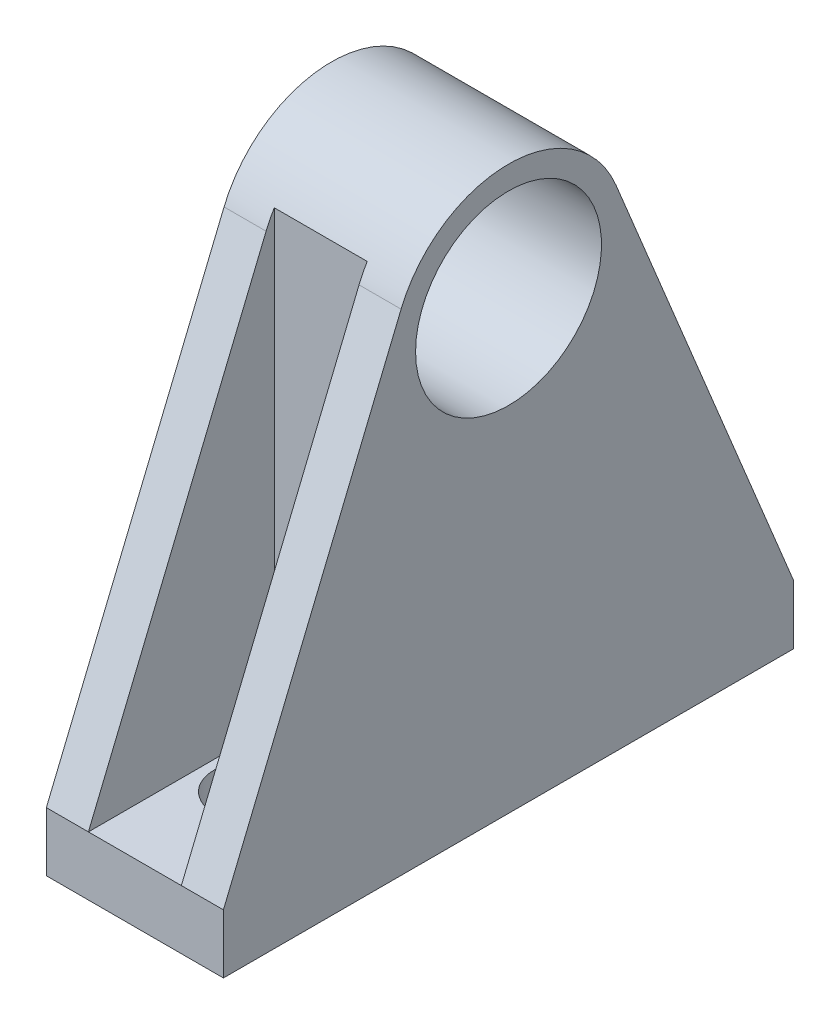
SolidWorks part; units mm, degrees
ref_plane "Front Plane" through (0, 0, 0) normal (0, 0, 1) x (1, 0, 0)
ref_plane "Top Plane" through (0, 0, 0) normal (0, 1, 0) x (1, 0, 0)
ref_plane "Right Plane" through (0, 0, 0) normal (1, 0, 0) x (0, 0, -1)
sketch "Sketch1" plane through (0, 0, 0) normal (1, 0, 0) x (0, 0, -1)
  line L0 (0, 0) -> (0, 48) construction
  line L5 (-30.675, 0) -> (-30.675, 6.35)
  line L8 (30.675, 0) -> (30.675, 6.35)
  line L11 (-30.675, 6.35) -> (-11.5579, 52.7608)
  line L12 (30.675, 6.35) -> (11.5579, 52.7608)
  line L13 (-30.675, 0) -> (30.675, 0)
  circle A0 centre (0, 48) radius 10
  arc A1 (11.5579, 52.7608) -> (-11.5579, 52.7608) centre (0, 48) ccw
  dimension "D1" = 48
  dimension "D2" = 20
  dimension "D3" = 25
  dimension "D4" = 6.35
  dimension "D5" = 30.675
extrude "Boss-Extrude1" add sketch "Sketch1" along normal blind 19.05
ref_plane "Plane1" through (9.525, 0, 0) normal (1, 0, 0) x (0, 0, -1)
sketch "Sketch2" plane through (0, 0, 0) normal (0, 1, 0) x (1, 0, 0)
  line L0 (9.525, -30.675) -> (9.525, 30.675) construction
  line L3 (0, 0) -> (19.05, 0) construction
  line L4 (19.05, -11.5579) -> (19.05, 11.5579) construction
  line L5 (19.05, -30.675) -> (0, -30.675) construction
  line L6 (0, -30.675) -> (19.05, -30.675) construction
  circle A0 centre (9.525, -18.175) radius 4
  circle A1 centre (9.525, 18.175) radius 4
  point P16 (17.5099, -30.675)
  point P18 (0, 0)
  point P19 (9.525, -30.675)
  dimension "D1" = 12.5
  dimension "D2" = 8
extrude "Cut-Extrude1" cut sketch "Sketch2" against normal mid plane 167.2722
sketch "Sketch3" plane through (9.525, 0, 0) normal (1, 0, 0) x (0, 0, -1)
  line L0 (-10.675, 54.9042) -> (-10.675, 6.35)
  line L1 (-10.675, 6.35) -> (-30.675, 6.35)
  line L3 (-11.5579, 52.7608) -> (-30.675, 6.35) construction
  line L4 (0, 60.5) -> (0, 0) construction
  line L5 (-10.675, 54.9042) -> (-30.675, 6.35)
  line L6 (10.675, 54.9042) -> (30.675, 6.35)
  line L7 (10.675, 6.35) -> (30.675, 6.35)
  line L8 (10.675, 54.9042) -> (10.675, 6.35)
  arc A1 (11.5579, 52.7608) -> (-11.5579, 52.7608) centre (0, 48) ccw construction
  dimension "D1" = 20
extrude "Cut-Extrude2" cut sketch "Sketch3" against normal mid plane 10
